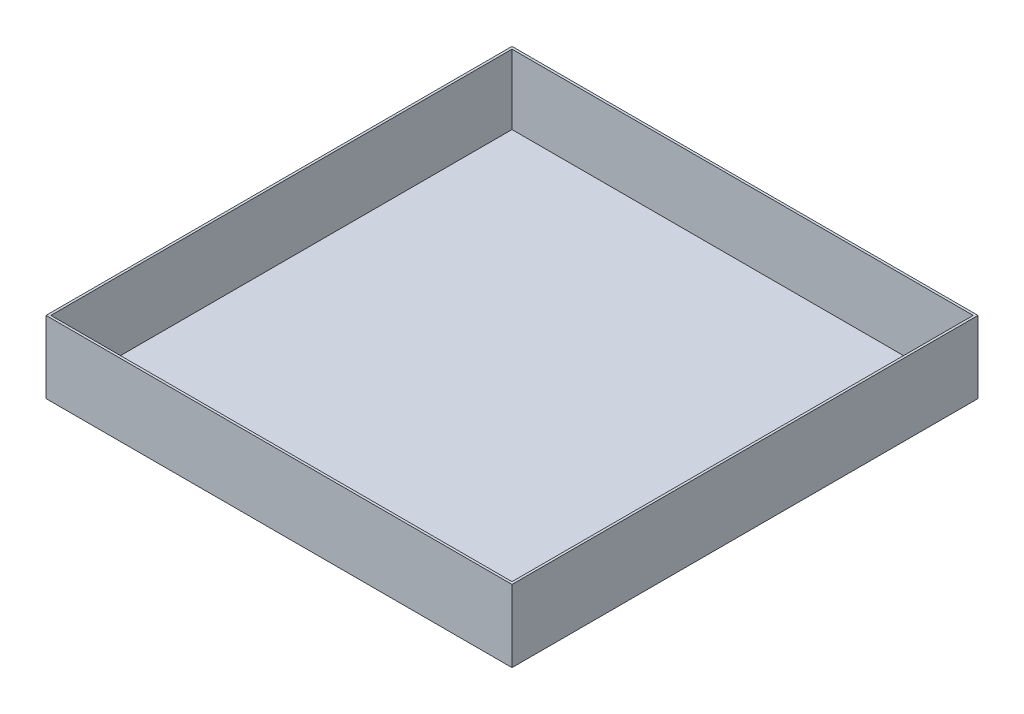
SolidWorks part; units mm, degrees
ref_plane "前视基准面" through (0, 0, 0) normal (0, 0, 1) x (1, 0, 0)
ref_plane "上视基准面" through (0, 0, 0) normal (0, 1, 0) x (1, 0, 0)
ref_plane "右视基准面" through (0, 0, 0) normal (1, 0, 0) x (0, 0, -1)
sketch "草图1" plane through (0, 0, 0) normal (0, 1, 0) x (1, 0, 0)
  line L1 (0, 0) -> (194, 0)
  line L2 (0, 0) -> (0, 194)
  line L3 (0, 194) -> (194, 194)
  line L4 (194, 0) -> (194, 194)
  dimension "D1" = 194
  dimension "D2" = 194
extrude "凸台-拉伸1" add sketch "草图1" along normal blind 30
shell "抽壳1" thickness 1
